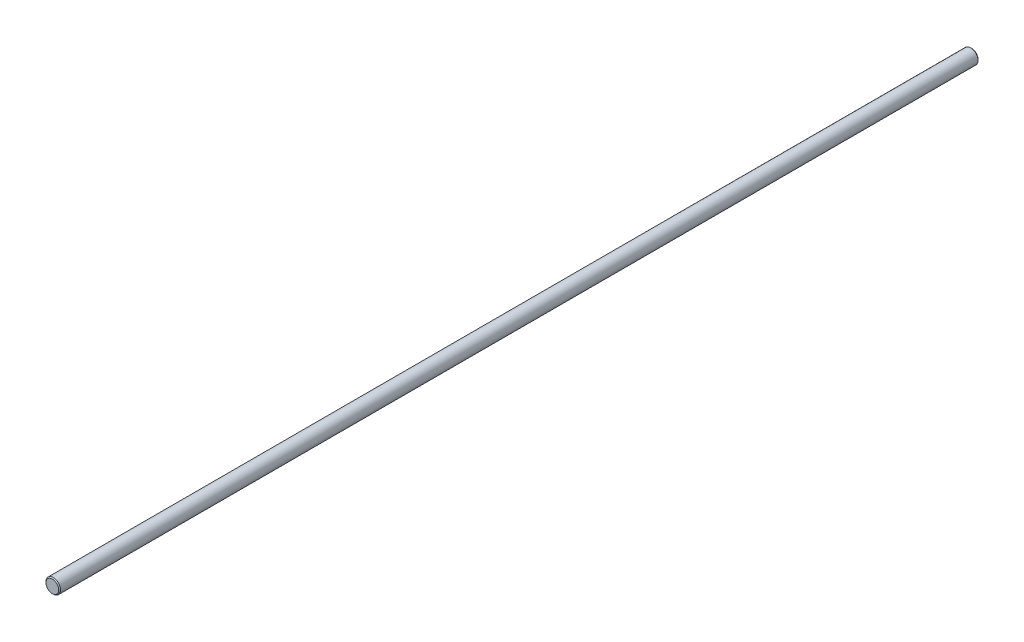
SolidWorks part; units mm, degrees
ref_plane "Front Plane" through (0, 0, 0) normal (0, 0, 1) x (1, 0, 0)
ref_plane "Top Plane" through (0, 0, 0) normal (0, 1, 0) x (1, 0, 0)
ref_plane "Right Plane" through (0, 0, 0) normal (1, 0, 0) x (0, 0, -1)
sketch "Sketch1" plane through (0, 0, 0) normal (0, 0, 1) x (1, 0, 0)
  circle A0 centre (0, 0) radius 3.95
  dimension "D1" = 7.9
extrude "Boss-Extrude1" add sketch "Sketch1" along normal blind 500
chamfer "Chamfer1" distance 0.5 angle 45 2 edges at (3.95, 0, 500) (3.95, 0, 0)
